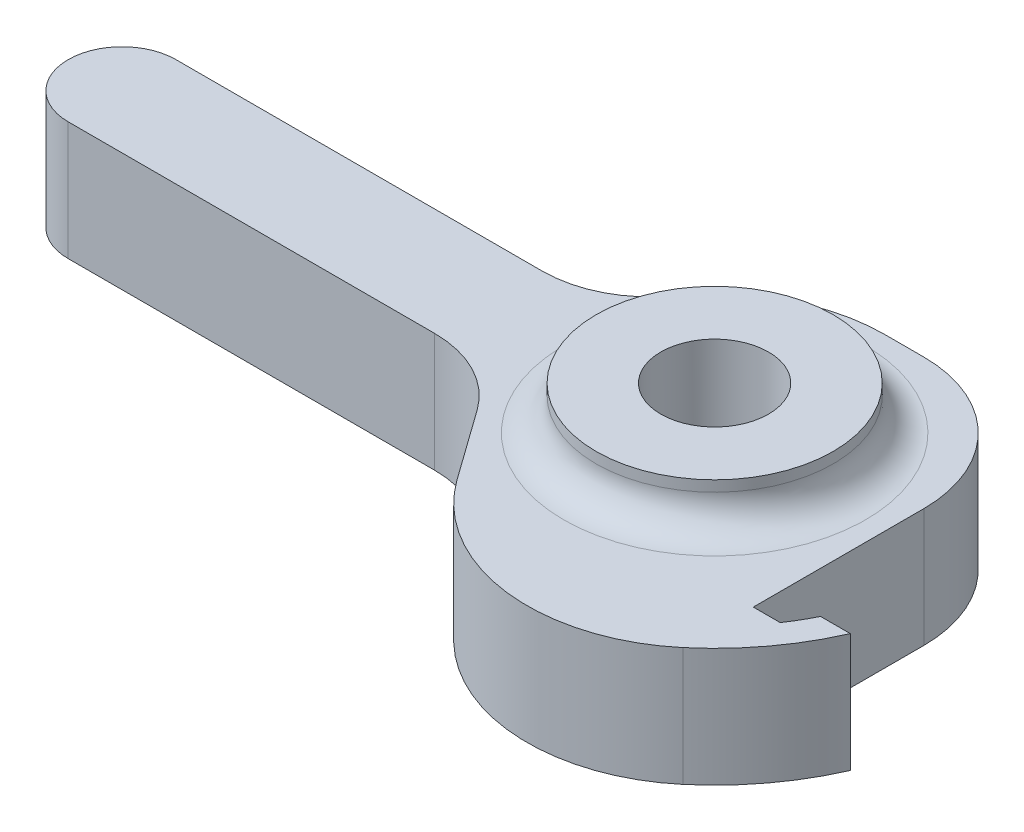
SolidWorks part; units mm, degrees
ref_plane "Front Plane" through (0, 0, 0) normal (0, 0, 1) x (1, 0, 0)
ref_plane "Top Plane" through (0, 0, 0) normal (0, 1, 0) x (1, 0, 0)
ref_plane "Right Plane" through (0, 0, 0) normal (1, 0, 0) x (0, 0, -1)
ref_plane "Plane1" through (0, -76.7336, 0) normal (0, -1, 0) x (-1, 0, 0)
sketch "Sketch1" plane through (0, -76.7336, 0) normal (0, 1, 0) x (1, 0, 0)
  line L0 (88.3412, 19.9) -> (88.3412, 13.8107) construction
  line L1 (88.3412, 19.9) -> (82.2519, 19.9) construction
  line L2 (52.9412, 9.5) -> (69.9455, 9.5)
  line L6 (80.4412, 12) -> (50.4412, 12) construction
  line L7 (52.9412, 14.5) -> (69.9455, 14.5)
  line L8 (86.5577, 18.1165) -> (86.0274, 17.5861) construction
  line L9 (82.2519, 19.9) -> (80.4412, 19.9)
  line L10 (88.3412, 13.8107) -> (88.3412, 12)
  line L11 (91.6588, 7.0779) -> (90.2785, 7.0779)
  line L12 (89.5912, 5.8945) -> (88.3412, 5.8945)
  line L13 (88.3412, 5.8945) -> (88.3412, 12)
  line L14 (74.0136, 7.407) -> (76.347, 4.1416)
  circle A0 centre (80.4412, 12) radius 2.5 construction
  circle A1 centre (80.4412, 12) radius 2.5
  arc A2 (80.4412, 19.9) -> (74.0136, 16.593) centre (80.4412, 12) ccw
  arc A3 (88.3412, 12) -> (80.4412, 19.9) centre (80.4412, 12) ccw construction
  arc A4 (52.9412, 14.5) -> (52.9412, 9.5) centre (52.9412, 12) ccw
  arc A5 (69.9455, 14.5) -> (74.0136, 16.593) centre (69.9455, 19.5) ccw
  arc A6 (69.9455, 9.5) -> (74.0136, 7.407) centre (69.9455, 4.5) cw
  arc A7 (52.9412, 9.5) -> (52.9412, 14.5) centre (52.9412, 12) ccw construction
  arc A8 (74.0136, 16.593) -> (74.0136, 7.407) centre (80.4412, 12) ccw construction
  arc A14 (80.4412, 4.1) -> (88.3412, 12) centre (80.4412, 12) ccw construction
  circle A15 centre (80.4412, 12) radius 7.9 construction
  circle A16 centre (80.4412, 12) radius 12.25 construction
  arc A17 (88.3412, 13.8107) -> (82.2519, 19.9) centre (82.2519, 13.8107) ccw
  circle A18 centre (80.4412, 12) radius 11 construction
  arc A19 (90.2785, 7.0779) -> (89.5912, 5.8945) centre (80.4412, 12) cw
  arc A20 (91.6588, 7.0779) -> (88.3412, 2.6377) centre (80.4412, 12) cw
  arc A21 (88.3412, 2.6377) -> (76.347, 4.1416) centre (83.0379, 8.9227) cw
  point P25 (80.4412, 4.1)
  point P31 (79.7182, 1.855)
  point P33 (0, 0)
  point P34 (88.3412, 11.9489)
  dimension "D1" = 5
  dimension "D2" = 5
  dimension "D4" = 0.75
  dimension "D6" = 22
  dimension "D7" = 24.5
  dimension "D8" = 4.9221
  dimension "D3" = 30
  dimension "D5" = 7.9
  dimension "D10" = 6.1055
extrude "Boss-Extrude1" add sketch "Sketch1" against normal blind 5.5 from offset 2 offset against normal yes
sketch "Sketch2" plane through (0, -76.7336, 0) normal (0, -1, 0) x (-1, 0, 0)
  circle A0 centre (-80.4412, 12) radius 2.5 construction
  circle A1 centre (-80.4412, 12) radius 2.5
  circle A2 centre (-80.4412, 12) radius 5.5
  dimension "D1" = 3
extrude "Boss-Extrude2" add sketch "Sketch2" along normal up to next
fillet "Fillet1" radius 1.5 1 edges at (80.4412, -78.7336, -6.5)
